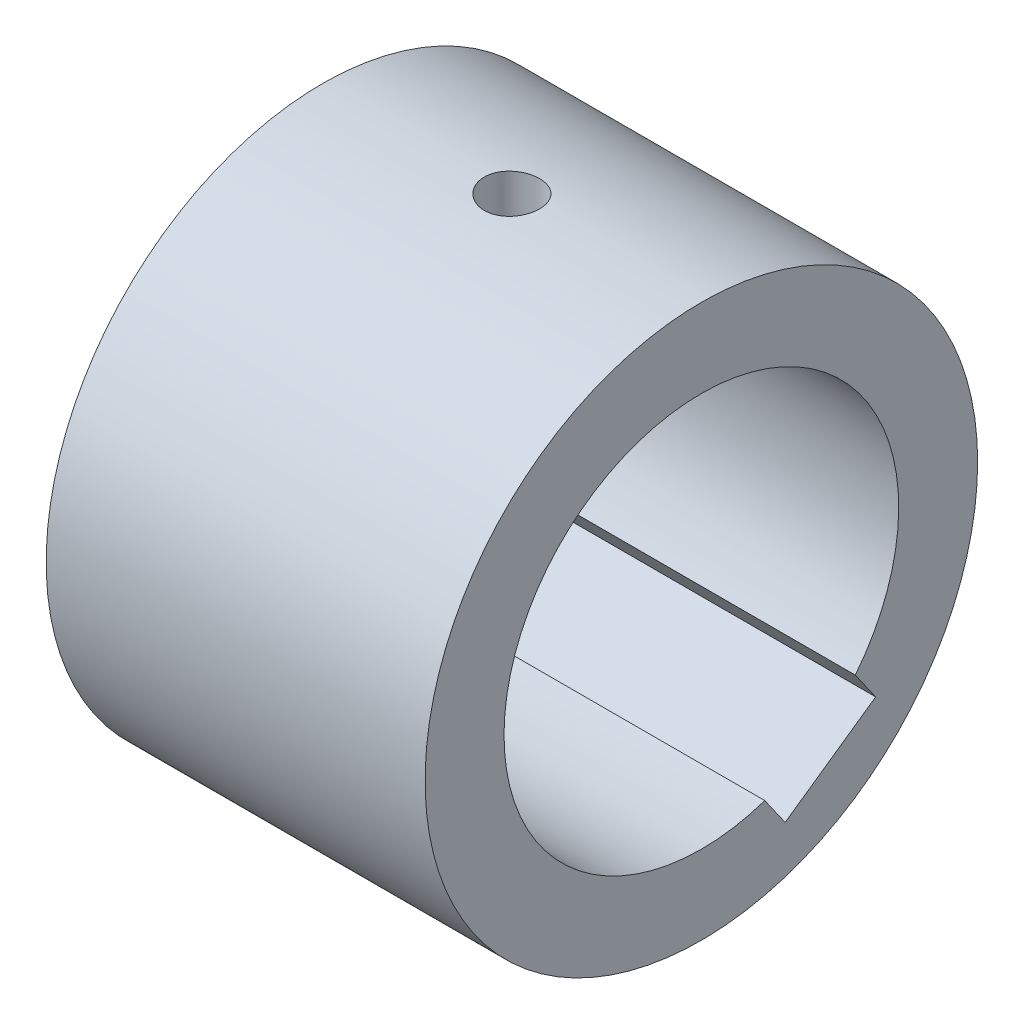
SolidWorks part; units mm, degrees
material "ASTM A36"
ref_plane "Front Plane" through (0, 0, 0) normal (0, 0, 1) x (1, 0, 0)
ref_plane "Top Plane" through (0, 0, 0) normal (0, 1, 0) x (1, 0, 0)
ref_plane "Right Plane" through (0, 0, 0) normal (1, 0, 0) x (0, 0, -1)
sketch "Sketch1" plane through (0, 0, 0) normal (1, 0, 0) x (0, 0, -1)
  circle A0 centre (0, 0) radius 25
  circle A1 centre (0, 0) radius 35
  dimension "D1" = 50
  dimension "D2" = 70
extrude "Boss-Extrude1" add sketch "Sketch1" along normal mid plane 48
sketch "Sketch5" plane through (24, 0, 0) normal (1, 0, 0) x (0, 0, -1)
  line L0 (0, 0) -> (17.3893, -24.8345) construction
  line L1 (22.081, -19.3308) -> (10.6129, -27.3609)
  line L2 (10.6129, -27.3609) -> (2.6183, -15.9435)
  line L3 (2.6183, -15.9435) -> (14.0865, -7.9134)
  line L4 (14.0865, -7.9134) -> (22.081, -19.3308)
  line L5 (0, 0) -> (19.9004, 0) construction
  point P4 (16.3469, -23.3458)
  dimension "D1" = 305
  dimension "D2" = 14
  dimension "D3" = 28.5
extrude "Cut-Extrude2" cut sketch "Sketch5" against normal through all
ref_plane "Plane1" through (0, 35, 0) normal (0, 1, 0) x (-1, 0, 0)
sketch "Sketch6" plane through (0, 35, 0) normal (0, 1, 0) x (-1, 0, 0)
  circle A0 centre (0, 0) radius 3.5
  dimension "D1" = 7
extrude "Cut-Extrude3" cut sketch "Sketch6" against normal blind 24
cosmetic thread "Cosmetic Thread1" parameters "D2"=8
